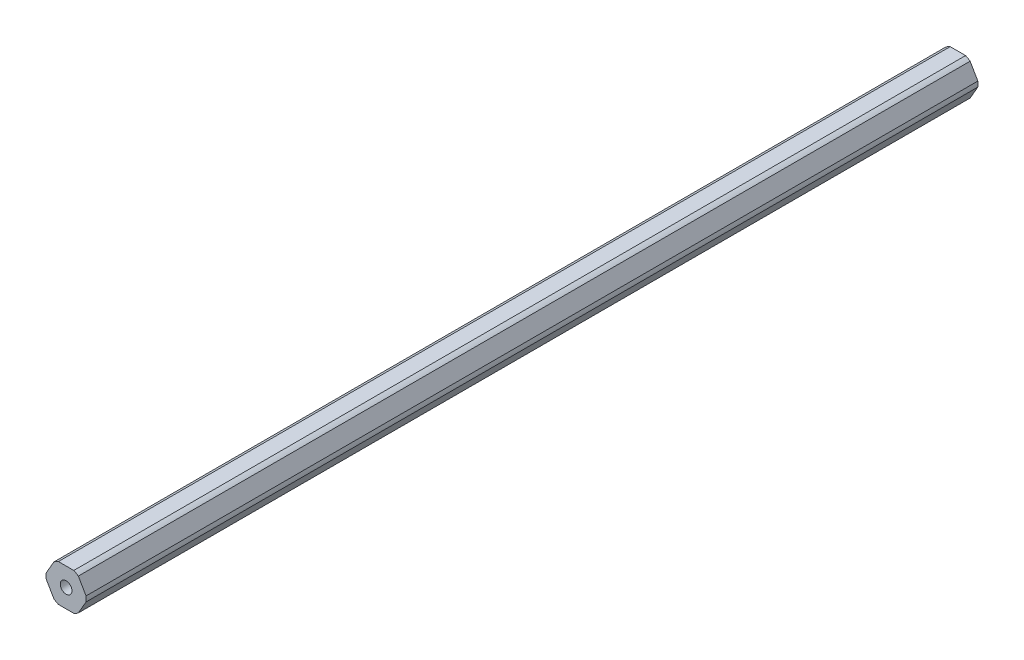
SolidWorks part; units mm, degrees
material "6061-T6 (SS)"
ref_plane "Front Plane" through (0, 0, 0) normal (0, 0, 1) x (1, 0, 0)
ref_plane "Top Plane" through (0, 0, 0) normal (0, 1, 0) x (1, 0, 0)
ref_plane "Right Plane" through (0, 0, 0) normal (1, 0, 0) x (0, 0, -1)
sketch "Sketch1" plane through (0, 0, 0) normal (0, 0, 1) x (1, 0, 0)
  line L1 (3.6662, 6.35) -> (-3.6662, 6.35)
  line L2 (-3.6662, 6.35) -> (-7.3323, 0)
  line L3 (-7.3323, 0) -> (-3.6662, -6.35)
  line L4 (-3.6662, -6.35) -> (3.6662, -6.35)
  line L5 (3.6662, -6.35) -> (7.3323, 0)
  line L6 (7.3323, 0) -> (3.6662, 6.35)
  circle A0 centre (0, 0) radius 6.35 construction
  circle A1 centre (0, 0) radius 2
  circle A2 centre (0, 0) radius 6.875
  point P1 (0, 6.35)
  dimension "D2" = 13.75
  dimension "D3" = 4
  dimension "D1" = 12.7
extrude "Boss-Extrude1" add sketch "Sketch1" along normal mid plane 304.8 contours L6 A2 L1 L2 L3 L4 L5 A1
sketch "Sketch4" plane through (0, 0, 152.4) normal (0, 0, 1) x (1, 0, 0)
  circle A0 centre (0, 0) radius 6.35
  circle A2 centre (0, 0) radius 2.4892
  dimension "D1" = 12.7
  dimension "D2" = 4.9784
equation "\"D2@Sketch1\"=13.75mm"
equation "\"D3@Sketch1\"=4mm"
